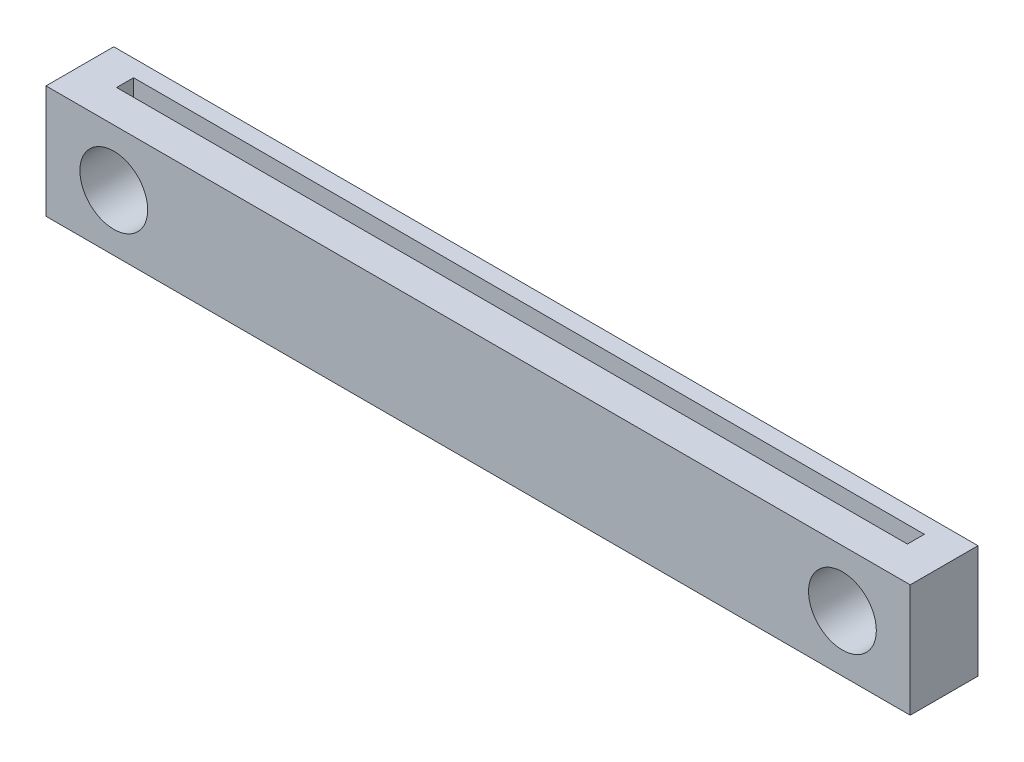
SolidWorks part; units mm, degrees
ref_plane "前视基准面" through (0, 0, 0) normal (0, 0, 1) x (1, 0, 0)
ref_plane "上视基准面" through (0, 0, 0) normal (0, 1, 0) x (1, 0, 0)
ref_plane "右视基准面" through (0, 0, 0) normal (1, 0, 0) x (0, 0, -1)
other "Configuration Table"
sketch "草图1" plane through (0, 0, 0) normal (0, 0, 1) x (1, 0, 0)
  line L0 (0, 0) -> (53297.0319, 0) construction
  line L1 (0, 0) -> (0, 53297.0319) construction
  line L3 (-35, 5) -> (35, 5)
  line L4 (-35, 5) -> (-35, -5)
  line L5 (-35, -5) -> (35, -5)
  line L6 (35, 5) -> (35, -5)
  dimension "D1" = 70
  dimension "D2" = 10
extrude "凸台-拉伸1" add sketch "草图1" along normal blind 6
sketch "草图2" plane through (-35, 0, 0) normal (-1, 0, 0) x (0, 0, 1)
  line L0 (1.5, 5) -> (1.5, 3.5)
  line L1 (6, 5) -> (0, 5) construction
  line L2 (1.5, 3.5) -> (3, 3.5)
  line L3 (3, 3.5) -> (3, 5)
  line L4 (1.5, -5) -> (1.5, -3.5)
  line L5 (6, -5) -> (0, -5) construction
  line L6 (1.5, -3.5) -> (3, -3.5)
  line L7 (3, -3.5) -> (3, -5)
  line L8 (0, -5.5) -> (0, 5.5) construction
  line L9 (1.5, 5) -> (3, 5)
  line L10 (1.5, -5) -> (3, -5)
  dimension "D1" = 1.5
  dimension "D2" = 1.5
  dimension "D3" = 1.5
  dimension "D4" = 1.5
  dimension "D5" = 1.5
extrude "切除-拉伸1" cut sketch "草图2" against normal through all contours L9 L3 L2 L0 | L10 L7 L6 L4
sketch "草图3" plane through (0, 0, 6) normal (0, 0, 1) x (1, 0, 0)
  line L0 (0, 0) -> (50000, 0) construction
  line L1 (0, 0) -> (0, 50000) construction
  line L2 (-35, 5) -> (-35, -5) construction
  line L3 (35, -5) -> (35, 5) construction
  circle A0 centre (-29, 0) radius 3
  circle A1 centre (29, 0) radius 3
  dimension "D1" = 6
  dimension "D2" = 6
extrude "切除-拉伸2" cut sketch "草图3" against normal through all contours A0 | A1
sketch "草图4" plane through (0, 0, 6) normal (0, 0, 1) x (1, 0, 0)
  line L0 (0, 0) -> (50000, 0) construction
  line L1 (0, 0) -> (0, 50000) construction
  circle A0 centre (-29, 0) radius 3
  circle A1 centre (-32.25, 0) radius 3
  circle A2 centre (32.25, 0) radius 3
  dimension "D1" = 3.25
extrude "切除-拉伸3" cut sketch "草图4" against normal through all contours A1
sketch "草图5" plane through (0, 0, 6) normal (0, 0, 1) x (1, 0, 0)
  line L0 (0, 0) -> (50000, 0) construction
  line L1 (0, 0) -> (0, 50000) construction
  line L2 (38.25, -5) -> (38.25, 5)
  line L3 (-35, -5) -> (-38.25, -5)
  line L4 (-35, -5) -> (-35, 5)
  line L5 (-35, 5) -> (-38.25, 5)
  line L6 (-38.25, -5) -> (-38.25, 5)
  line L7 (35, -5) -> (38.25, -5)
  line L8 (35, -5) -> (35, 5)
  line L9 (35, 5) -> (38.25, 5)
extrude "凸台-拉伸2" add sketch "草图5" against normal blind 6
sketch "草图9" plane through (0, 0, 6) normal (0, 0, 1) x (1, 0, 0)
  line L0 (0, 0) -> (50000, 0) construction
  line L1 (0, 0) -> (0, 50000) construction
  circle A0 centre (-29, 0) radius 3
  circle A1 centre (-32.25, 0) radius 3
  circle A2 centre (32.25, 0) radius 3
  arc M7 (-35, 1.199) -> (-30.625, 2.5218) centre (-32.25, 0) cw
  arc M9 (-30.625, -2.5218) -> (-35, -1.199) centre (-32.25, 0) cw
  line M10 (-35, -1.199) -> (-35, 1.199)
  circle M11 centre (29, 0) radius 3
  dimension "D1" = 3.25
extrude "切除-拉伸4" cut sketch "草图9" against normal through all contours A0 M7 M10 M9 | A1 M10 | A0 A1 | A2 M11 | A2 M11
sketch "草图10" plane through (0, 0, 6) normal (0, 0, 1) x (1, 0, 0)
  circle A0 centre (-29, 0) radius 3
  circle A1 centre (29, 0) radius 3
extrude "凸台-拉伸4" add sketch "草图10" against normal blind 6
sketch "草图11" plane through (0, 0, 6) normal (0, 0, 1) x (1, 0, 0)
  line L0 (0, 0) -> (50000, 0) construction
  circle A0 centre (-32.25, 0) radius 3
  circle A1 centre (32.25, 0) radius 3
extrude "切除-拉伸5" cut sketch "草图11" against normal through all
